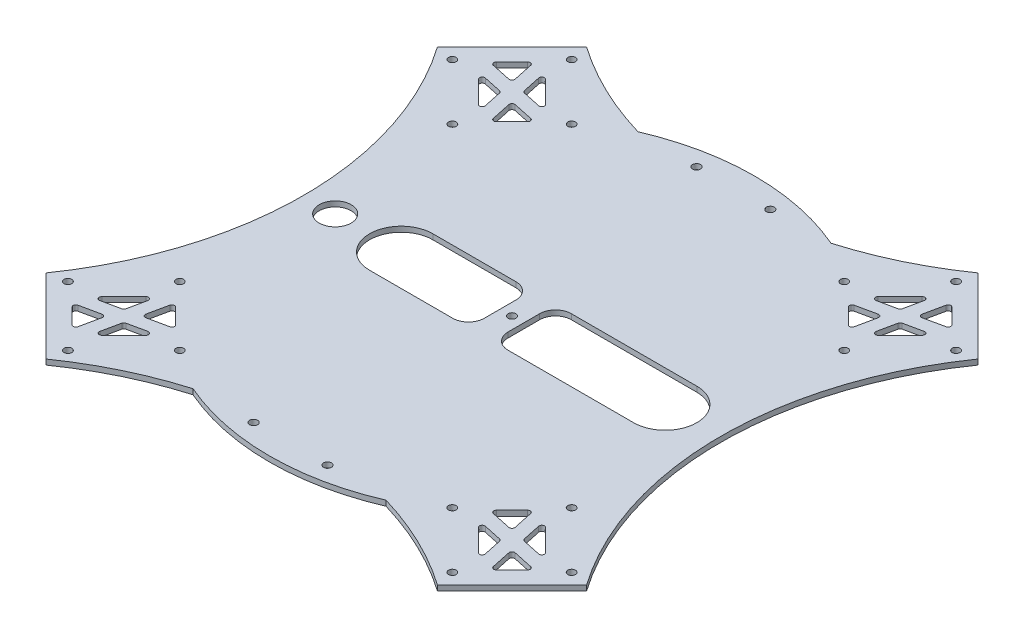
SolidWorks part; units mm, degrees
material "Thornel Mat VMA"
ref_plane "前视基准面" through (0, 0, 0) normal (0, 0, 1) x (1, 0, 0)
ref_plane "上视基准面" through (0, 0, 0) normal (0, 1, 0) x (1, 0, 0)
ref_plane "右视基准面" through (0, 0, 0) normal (1, 0, 0) x (0, 0, -1)
sketch "草图1" plane through (0, 0, 0) normal (0, 1, 0) x (1, 0, 0)
  line L0 (-74.2462, 102.5305) -> (-102.5305, 74.2462)
  line L1 (74.2462, 102.5305) -> (-74.2462, 102.5305)
  line L2 (102.5305, 74.2462) -> (102.5305, -74.2462)
  line L3 (74.2462, -102.5305) -> (-74.2462, -102.5305)
  line L4 (-102.5305, 74.2462) -> (-102.5305, -74.2462)
  line L5 (102.5305, 102.5305) -> (-102.5305, -102.5305) construction
  line L6 (102.5305, -102.5305) -> (-102.5305, 102.5305) construction
  line L7 (102.5305, -74.2462) -> (74.2462, -102.5305)
  line L8 (-102.5305, -74.2462) -> (-74.2462, -102.5305)
  line L9 (74.2462, 102.5305) -> (102.5305, 74.2462)
  line L10 (-102.5305, 102.5305) -> (-102.5305, -102.5305) construction
  line L11 (-102.5305, -102.5305) -> (102.5305, -102.5305) construction
  line L12 (102.5305, -102.5305) -> (102.5305, 102.5305) construction
  line L13 (102.5305, 102.5305) -> (-102.5305, 102.5305) construction
  point P0 (0, 0)
  dimension "D1" = 250
  dimension "D2" = 40
extrude "凸台-拉伸1" add sketch "草图1" along normal blind 2
hole_wizard "孔1" positions "草图4" profile "草图5" legacy
sketch "草图4" plane through (0, 2, 0) normal (0, 1, 0) x (1, 0, 0)
  point P0 (-95.5397, 72.9159)
  point P3 (-74.3265, 51.7027)
  point P6 (-51.6991, 74.3301)
  point P9 (-72.9123, 95.5433)
  point P16 (72.9159, 95.5397)
  point P17 (51.7027, 74.3265)
  point P18 (74.3301, 51.6991)
  point P19 (95.5433, 72.9123)
  point P20 (95.5397, -72.9159)
  point P21 (74.3265, -51.7027)
  point P22 (51.6991, -74.3301)
  point P23 (72.9123, -95.5433)
  point P24 (-72.9159, -95.5397)
  point P25 (-51.7027, -74.3265)
  point P26 (-74.3301, -51.6991)
  point P27 (-95.5433, -72.9123)
  dimension "D1" = 4
sketch "草图5" plane through (-95.5397, 2, -72.9159) normal (1, 0, 0) x (0, 0, 1)
  line L0 (0, 0) -> (0, 100)
  line L1 (0, 100) -> (1.45, 100)
  line L2 (1.45, 100) -> (1.45, 0)
  line L3 (1.45, 0) -> (0, 0)
  line L4 (0, 110) -> (0, -10) construction
  dimension "直径" = 2.9
  dimension "深度" = 100
sketch "草图7" plane through (0, 2, 0) normal (0, 1, 0) x (1, 0, 0)
  line L0 (-95.5397, 72.9159) -> (-51.6991, 74.3301) construction
  line L1 (-86.393, 80.4842) -> (-80.4806, 86.3966)
  line L2 (-84.1601, 71.4358) -> (-75.8066, 63.0823)
  line L3 (-71.4322, 84.1637) -> (-63.0787, 75.8102)
  line L4 (-66.7582, 60.8494) -> (-60.8458, 66.7618)
  line L5 (-89.8008, 77.0764) -> (-57.438, 70.1696) construction
  line L6 (-77.0728, 89.8044) -> (-70.166, 57.4416) construction
  line L7 (-49.2242, 67.6126) -> (-79.6109, 97.9993) construction
  line L8 (-74.2462, 102.5305) -> (-102.5305, 74.2462) construction
  line L9 (-85.8946, 78.7991) -> (-78.378, 77.1949)
  line L10 (-83.2443, 73.1208) -> (-76.36, 71.6516)
  line L11 (-87.6941, 79.1831) -> (-89.8008, 77.0764) construction
  line L12 (-89.8008, 77.0764) -> (-86.5509, 73.8265) construction
  line L13 (-60.6879, 73.4195) -> (-57.438, 70.1696) construction
  line L14 (-57.438, 70.1696) -> (-59.5447, 68.0629) construction
  line L15 (-67.4604, 74.8648) -> (-68.504, 69.975) construction
  line L16 (-73.6194, 73.623) -> (-67.2554, 79.987) construction
  line L17 (-74.1216, 63.9981) -> (-75.5908, 70.8824)
  line L18 (-68.4433, 61.3478) -> (-70.0475, 68.8644)
  line L19 (-70.8788, 75.5944) -> (-63.9945, 74.1252)
  line L20 (-77.1913, 78.3816) -> (-78.7955, 85.8982)
  line L21 (-68.8608, 70.0511) -> (-61.3442, 68.4469)
  line L22 (-71.648, 76.3636) -> (-73.1172, 83.2479)
  line L23 (80.4842, 86.393) -> (86.3966, 80.4806)
  line L24 (71.4358, 84.1601) -> (63.0823, 75.8066)
  line L25 (84.1637, 71.4322) -> (75.8102, 63.0787)
  line L26 (60.8494, 66.7582) -> (66.7618, 60.8458)
  line L27 (78.7991, 85.8946) -> (77.1949, 78.378)
  line L28 (73.1208, 83.2443) -> (71.6516, 76.36)
  line L29 (63.9981, 74.1216) -> (70.8824, 75.5908)
  line L30 (61.3478, 68.4433) -> (68.8644, 70.0475)
  line L31 (75.5944, 70.8788) -> (74.1252, 63.9945)
  line L32 (78.3816, 77.1913) -> (85.8982, 78.7955)
  line L33 (70.0511, 68.8608) -> (68.4469, 61.3442)
  line L34 (76.3636, 71.648) -> (83.2479, 73.1172)
  line L35 (72.9159, 95.5397) -> (74.3301, 51.6991) construction
  line L36 (77.0764, 89.8008) -> (70.1696, 57.438) construction
  line L37 (89.8044, 77.0728) -> (57.4416, 70.166) construction
  line L38 (79.1831, 87.6941) -> (77.0764, 89.8008) construction
  line L39 (77.0764, 89.8008) -> (73.8265, 86.5509) construction
  line L40 (73.4195, 60.6879) -> (70.1696, 57.438) construction
  line L41 (70.1696, 57.438) -> (68.0629, 59.5447) construction
  line L42 (74.8648, 67.4604) -> (69.975, 68.504) construction
  line L43 (73.623, 73.6194) -> (79.987, 67.2554) construction
  line L44 (86.393, -80.4842) -> (80.4806, -86.3966)
  line L45 (84.1601, -71.4358) -> (75.8066, -63.0823)
  line L46 (71.4322, -84.1637) -> (63.0787, -75.8102)
  line L47 (66.7582, -60.8494) -> (60.8458, -66.7618)
  line L48 (85.8946, -78.7991) -> (78.378, -77.1949)
  line L49 (83.2443, -73.1208) -> (76.36, -71.6516)
  line L50 (74.1216, -63.9981) -> (75.5908, -70.8824)
  line L51 (68.4433, -61.3478) -> (70.0475, -68.8644)
  line L52 (70.8788, -75.5944) -> (63.9945, -74.1252)
  line L53 (77.1913, -78.3816) -> (78.7955, -85.8982)
  line L54 (68.8608, -70.0511) -> (61.3442, -68.4469)
  line L55 (71.648, -76.3636) -> (73.1172, -83.2479)
  line L56 (95.5397, -72.9159) -> (51.6991, -74.3301) construction
  line L57 (89.8008, -77.0764) -> (57.438, -70.1696) construction
  line L58 (77.0728, -89.8044) -> (70.166, -57.4416) construction
  line L59 (87.6941, -79.1831) -> (89.8008, -77.0764) construction
  line L60 (89.8008, -77.0764) -> (86.5509, -73.8265) construction
  line L61 (60.6879, -73.4195) -> (57.438, -70.1696) construction
  line L62 (57.438, -70.1696) -> (59.5447, -68.0629) construction
  line L63 (67.4604, -74.8648) -> (68.504, -69.975) construction
  line L64 (73.6194, -73.623) -> (67.2554, -79.987) construction
  line L65 (-80.4842, -86.393) -> (-86.3966, -80.4806)
  line L66 (-71.4358, -84.1601) -> (-63.0823, -75.8066)
  line L67 (-84.1637, -71.4322) -> (-75.8102, -63.0787)
  line L68 (-60.8494, -66.7582) -> (-66.7618, -60.8458)
  line L69 (-78.7991, -85.8946) -> (-77.1949, -78.378)
  line L70 (-73.1208, -83.2443) -> (-71.6516, -76.36)
  line L71 (-63.9981, -74.1216) -> (-70.8824, -75.5908)
  line L72 (-61.3478, -68.4433) -> (-68.8644, -70.0475)
  line L73 (-75.5944, -70.8788) -> (-74.1252, -63.9945)
  line L74 (-78.3816, -77.1913) -> (-85.8982, -78.7955)
  line L75 (-70.0511, -68.8608) -> (-68.4469, -61.3442)
  line L76 (-76.3636, -71.648) -> (-83.2479, -73.1172)
  line L77 (-72.9159, -95.5397) -> (-74.3301, -51.6991) construction
  line L78 (-77.0764, -89.8008) -> (-70.1696, -57.438) construction
  line L79 (-89.8044, -77.0728) -> (-57.4416, -70.166) construction
  line L80 (-79.1831, -87.6941) -> (-77.0764, -89.8008) construction
  line L81 (-77.0764, -89.8008) -> (-73.8265, -86.5509) construction
  line L82 (-73.4195, -60.6879) -> (-70.1696, -57.438) construction
  line L83 (-70.1696, -57.438) -> (-68.0629, -59.5447) construction
  line L84 (-74.8648, -67.4604) -> (-69.975, -68.504) construction
  line L85 (-73.623, -73.6194) -> (-79.987, -67.2554) construction
  arc A0 (-63.0787, 75.8102) -> (-63.9945, 74.1252) centre (-63.7858, 75.1031) cw
  arc A1 (-70.8788, 75.5944) -> (-71.648, 76.3636) centre (-70.67, 76.5724) cw
  arc A2 (-71.4322, 84.1637) -> (-73.1172, 83.2479) centre (-72.1393, 83.4566) ccw
  arc A3 (-78.7955, 85.8982) -> (-80.4806, 86.3966) centre (-79.7735, 85.6895) ccw
  arc A4 (-85.8946, 78.7991) -> (-86.393, 80.4842) centre (-85.6859, 79.7771) cw
  arc A5 (-78.378, 77.1949) -> (-77.1913, 78.3816) centre (-78.1693, 78.1729) ccw
  arc A6 (-66.7582, 60.8494) -> (-68.4433, 61.3478) centre (-67.4653, 61.5565) cw
  arc A7 (-60.8458, 66.7618) -> (-61.3442, 68.4469) centre (-61.5529, 67.4689) ccw
  arc A8 (-68.8608, 70.0511) -> (-70.0475, 68.8644) centre (-69.0695, 69.0731) ccw
  arc A9 (-75.8066, 63.0823) -> (-74.1216, 63.9981) centre (-75.0995, 63.7894) ccw
  arc A10 (-75.5908, 70.8824) -> (-76.36, 71.6516) centre (-76.5688, 70.6736) ccw
  arc A11 (-83.2443, 73.1208) -> (-84.1601, 71.4358) centre (-83.453, 72.1429) ccw
  arc A12 (75.8102, 63.0787) -> (74.1252, 63.9945) centre (75.1031, 63.7858) cw
  arc A13 (75.5944, 70.8788) -> (76.3636, 71.648) centre (76.5724, 70.67) cw
  arc A14 (84.1637, 71.4322) -> (83.2479, 73.1172) centre (83.4566, 72.1393) ccw
  arc A15 (85.8982, 78.7955) -> (86.3966, 80.4806) centre (85.6895, 79.7735) ccw
  arc A16 (78.7991, 85.8946) -> (80.4842, 86.393) centre (79.7771, 85.6859) cw
  arc A17 (77.1949, 78.378) -> (78.3816, 77.1913) centre (78.1729, 78.1693) ccw
  arc A18 (60.8494, 66.7582) -> (61.3478, 68.4433) centre (61.5565, 67.4653) cw
  arc A19 (66.7618, 60.8458) -> (68.4469, 61.3442) centre (67.4689, 61.5529) ccw
  arc A20 (70.0511, 68.8608) -> (68.8644, 70.0475) centre (69.0731, 69.0695) ccw
  arc A21 (63.0823, 75.8066) -> (63.9981, 74.1216) centre (63.7894, 75.0995) ccw
  arc A22 (70.8824, 75.5908) -> (71.6516, 76.36) centre (70.6736, 76.5688) ccw
  arc A23 (73.1208, 83.2443) -> (71.4358, 84.1601) centre (72.1429, 83.453) ccw
  arc A24 (63.0787, -75.8102) -> (63.9945, -74.1252) centre (63.7858, -75.1031) cw
  arc A25 (70.8788, -75.5944) -> (71.648, -76.3636) centre (70.67, -76.5724) cw
  arc A26 (71.4322, -84.1637) -> (73.1172, -83.2479) centre (72.1393, -83.4566) ccw
  arc A27 (78.7955, -85.8982) -> (80.4806, -86.3966) centre (79.7735, -85.6895) ccw
  arc A28 (85.8946, -78.7991) -> (86.393, -80.4842) centre (85.6859, -79.7771) cw
  arc A29 (78.378, -77.1949) -> (77.1913, -78.3816) centre (78.1693, -78.1729) ccw
  arc A30 (66.7582, -60.8494) -> (68.4433, -61.3478) centre (67.4653, -61.5565) cw
  arc A31 (60.8458, -66.7618) -> (61.3442, -68.4469) centre (61.5529, -67.4689) ccw
  arc A32 (68.8608, -70.0511) -> (70.0475, -68.8644) centre (69.0695, -69.0731) ccw
  arc A33 (75.8066, -63.0823) -> (74.1216, -63.9981) centre (75.0995, -63.7894) ccw
  arc A34 (75.5908, -70.8824) -> (76.36, -71.6516) centre (76.5688, -70.6736) ccw
  arc A35 (83.2443, -73.1208) -> (84.1601, -71.4358) centre (83.453, -72.1429) ccw
  arc A36 (-75.8102, -63.0787) -> (-74.1252, -63.9945) centre (-75.1031, -63.7858) cw
  arc A37 (-75.5944, -70.8788) -> (-76.3636, -71.648) centre (-76.5724, -70.67) cw
  arc A38 (-84.1637, -71.4322) -> (-83.2479, -73.1172) centre (-83.4566, -72.1393) ccw
  arc A39 (-85.8982, -78.7955) -> (-86.3966, -80.4806) centre (-85.6895, -79.7735) ccw
  arc A40 (-78.7991, -85.8946) -> (-80.4842, -86.393) centre (-79.7771, -85.6859) cw
  arc A41 (-77.1949, -78.378) -> (-78.3816, -77.1913) centre (-78.1729, -78.1693) ccw
  arc A42 (-60.8494, -66.7582) -> (-61.3478, -68.4433) centre (-61.5565, -67.4653) cw
  arc A43 (-66.7618, -60.8458) -> (-68.4469, -61.3442) centre (-67.4689, -61.5529) ccw
  arc A44 (-70.0511, -68.8608) -> (-68.8644, -70.0475) centre (-69.0731, -69.0695) ccw
  arc A45 (-63.0823, -75.8066) -> (-63.9981, -74.1216) centre (-63.7894, -75.0995) ccw
  arc A46 (-70.8824, -75.5908) -> (-71.6516, -76.36) centre (-70.6736, -76.5688) ccw
  arc A47 (-73.1208, -83.2443) -> (-71.4358, -84.1601) centre (-72.1429, -83.453) ccw
  point P5 (-73.6194, 73.623)
  point P14 (-72.9123, 95.5433)
  point P21 (-67.9822, 72.4199)
  point P38 (-71.5127, 75.7297)
  point P41 (-73.8229, 86.5545)
  point P44 (-79.1795, 87.6977)
  point P50 (-76.8693, 76.8729)
  point P53 (-68.0593, 59.5483)
  point P59 (-70.3695, 70.3731)
  point P62 (-73.4159, 60.6915)
  point P73 (73.623, 73.6194)
  point P84 (72.4199, 67.9822)
  point P126 (73.6194, -73.623)
  point P137 (67.9822, -72.4199)
  point P179 (-73.623, -73.6194)
  point P190 (-72.4199, -67.9822)
  point P230 (0, 0)
  dimension "D4" = 1
  dimension "D1" = 7
  dimension "D2" = 7
  dimension "D3" = 5
  dimension "D5" = 4
extrude "切除-拉伸2" cut sketch "草图7" against normal through all both and the other way through all
sketch "草图8" plane through (0, 2, 0) normal (0, 1, 0) x (1, 0, 0)
  line L0 (-208.5651, 0) -> (0, 0) construction
  line L1 (-102.5305, -74.2462) -> (-50.5427, 0) construction
  line L3 (0, 0) -> (-88.3883, -88.3883) construction
  line L4 (-102.5305, -74.2462) -> (-74.2462, -102.5305) construction
  line L5 (0, 102.5305) -> (0, -102.5305) construction
  line L6 (74.2462, 102.5305) -> (-74.2462, 102.5305) construction
  line L7 (-74.2462, -102.5305) -> (74.2462, -102.5305) construction
  circle A0 centre (-208.5651, 0) radius 129.4443
  circle A2 centre (0, 208.5651) radius 129.4443
  circle A3 centre (208.5651, 0) radius 129.4443
  circle A4 centre (0, -208.5651) radius 129.4443
  point P28 (0, 0)
  dimension "D1" = 10
  dimension "D2" = 4
extrude "切除-拉伸3" cut sketch "草图8" against normal through all both and the other way through all
sketch "草图9" plane through (0, 2, 0) normal (0, 1, 0) x (1, 0, 0)
  line L0 (0, 0) -> (-79.1207, 0) construction
  arc A0 (-102.5305, -74.2462) -> (-102.5305, 74.2462) centre (-208.5651, 0) ccw construction
  circle A1 centre (-67.0707, 0) radius 6.05
  point P8 (-73.1207, 0)
  dimension "D1" = 12.1
  dimension "D2" = 6
extrude "切除-拉伸4" cut sketch "草图9" against normal through all both and the other way through all
sketch "草图12" plane through (0, 2, 0) normal (0, 1, 0) x (1, 0, 0)
  line L0 (-74.2462, 102.5305) -> (-19.9669, 133.265)
  line L1 (-17.0105, 134.0438) -> (17.0105, 134.0438)
  line L2 (19.9669, 133.265) -> (74.2462, 102.5305)
  line L3 (0, 134.0438) -> (0, 0) construction
  line L4 (-74.2462, 102.5305) -> (-66.3304, 96.7253)
  line L5 (-62.6332, 98.7635) -> (-17.5957, 124.265)
  line L6 (-14.6394, 125.0438) -> (-10.5, 125.0438)
  line L7 (17.5957, 124.265) -> (62.6332, 98.7635)
  line L8 (66.1574, 95.9526) -> (74.2462, 102.5305)
  line L9 (-4.5, 119.0438) -> (-4.5, 81.2866)
  line L10 (-9.698, 64.0438) -> (9.698, 64.0438)
  line L11 (4.5, 81.2866) -> (4.5, 119.0438)
  line L12 (10.5, 125.0438) -> (14.6394, 125.0438)
  line L13 (-46.2735, 118.3694) -> (-41.839, 110.5377) construction
  line L14 (-4.5, 125.0438) -> (-4.5, 134.0438) construction
  line L15 (-66.3304, 96.7253) -> (-9.698, 64.0438)
  line L16 (9.698, 64.0438) -> (66.1574, 95.9526)
  line L17 (-4.5, 79.199) -> (4.5, 79.199) construction
  line L18 (-79.1207, 0) -> (79.1207, 0) construction
  line L19 (-4.5, -79.199) -> (4.5, -79.199) construction
  line L20 (-4.5, -125.0438) -> (-4.5, -134.0438) construction
  line L21 (-46.2735, -118.3694) -> (-41.839, -110.5377) construction
  line L22 (9.698, -64.0438) -> (66.1574, -95.9526)
  line L23 (-66.3304, -96.7253) -> (-9.698, -64.0438)
  line L24 (10.5, -125.0438) -> (14.6394, -125.0438)
  line L25 (4.5, -81.2866) -> (4.5, -119.0438)
  line L26 (-9.698, -64.0438) -> (9.698, -64.0438)
  line L27 (-4.5, -119.0438) -> (-4.5, -81.2866)
  line L28 (66.1574, -95.9526) -> (74.2462, -102.5305)
  line L29 (17.5957, -124.265) -> (62.6332, -98.7635)
  line L30 (-14.6394, -125.0438) -> (-10.5, -125.0438)
  line L31 (-62.6332, -98.7635) -> (-17.5957, -124.265)
  line L32 (-74.2462, -102.5305) -> (-66.3304, -96.7253)
  line L33 (19.9669, -133.265) -> (74.2462, -102.5305)
  line L34 (-17.0105, -134.0438) -> (17.0105, -134.0438)
  line L35 (-74.2462, -102.5305) -> (-19.9669, -133.265)
  arc A0 (-62.6152, 95.2727) -> (-6.602, 79.2892) centre (0, 208.5651) ccw
  arc A1 (-74.2462, 102.5305) -> (74.2462, 102.5305) centre (0, 208.5651) ccw construction
  arc A2 (6.602, 79.2892) -> (62.6152, 95.2727) centre (0, 208.5651) ccw
  arc A3 (-102.5305, -74.2462) -> (-102.5305, 74.2462) centre (-208.5651, 0) ccw construction
  arc A4 (102.5305, 74.2462) -> (102.5305, -74.2462) centre (208.5651, 0) ccw construction
  arc A5 (62.6152, 95.2727) -> (62.6332, 98.7635) centre (61.6478, 97.0231) ccw
  arc A6 (-62.6332, 98.7635) -> (-62.6152, 95.2727) centre (-61.6478, 97.0231) ccw
  arc A7 (6.602, 79.2892) -> (4.5, 81.2866) centre (6.5, 81.2866) cw
  arc A8 (-4.5, 81.2866) -> (-6.602, 79.2892) centre (-6.5, 81.2866) cw
  arc A9 (19.9669, 133.265) -> (17.0105, 134.0438) centre (17.0105, 128.0438) ccw
  arc A10 (-17.0105, 134.0438) -> (-19.9669, 133.265) centre (-17.0105, 128.0438) ccw
  arc A11 (-14.6394, 125.0438) -> (-17.5957, 124.265) centre (-14.6394, 119.0438) ccw
  arc A12 (17.5957, 124.265) -> (14.6394, 125.0438) centre (14.6394, 119.0438) ccw
  arc A13 (4.5, 119.0438) -> (10.5, 125.0438) centre (10.5, 119.0438) cw
  arc A14 (-4.5, 119.0438) -> (-10.5, 125.0438) centre (-10.5, 119.0438) ccw
  arc A15 (-4.5, -119.0438) -> (-10.5, -125.0438) centre (-10.5, -119.0438) cw
  arc A16 (4.5, -119.0438) -> (10.5, -125.0438) centre (10.5, -119.0438) ccw
  arc A17 (17.5957, -124.265) -> (14.6394, -125.0438) centre (14.6394, -119.0438) cw
  arc A18 (-14.6394, -125.0438) -> (-17.5957, -124.265) centre (-14.6394, -119.0438) cw
  arc A19 (-17.0105, -134.0438) -> (-19.9669, -133.265) centre (-17.0105, -128.0438) cw
  arc A20 (19.9669, -133.265) -> (17.0105, -134.0438) centre (17.0105, -128.0438) cw
  arc A21 (-4.5, -81.2866) -> (-6.602, -79.2892) centre (-6.5, -81.2866) ccw
  arc A22 (6.602, -79.2892) -> (4.5, -81.2866) centre (6.5, -81.2866) ccw
  arc A23 (-62.6332, -98.7635) -> (-62.6152, -95.2727) centre (-61.6478, -97.0231) cw
  arc A24 (62.6152, -95.2727) -> (62.6332, -98.7635) centre (61.6478, -97.0231) cw
  arc A25 (6.602, -79.2892) -> (62.6152, -95.2727) centre (0, -208.5651) cw
  arc A26 (-62.6152, -95.2727) -> (-6.602, -79.2892) centre (0, -208.5651) cw
  point P17 (0, 64.0438)
  point P24 (0, 79.199)
  point P40 (65.6946, 97.0301)
  point P43 (-65.6946, 97.0301)
  point P60 (4.5, 125.0438)
  point P107 (4.5, -125.0438)
  point P108 (-65.6946, -97.0301)
  point P109 (65.6946, -97.0301)
  point P110 (0, -79.199)
  point P111 (0, -64.0438)
  dimension "D4" = 2
  dimension "D5" = 2
  dimension "D6" = 6
  dimension "D1" = 70
  dimension "D2" = 9
  dimension "D3" = 9
sketch "草图15" plane through (0, 2, 0) normal (0, 1, 0) x (1, 0, 0)
  line L1 (-40.3412, 82.6837) -> (-31.9185, 62.6852)
  line L2 (44.6358, 80.4465) -> (36.2732, 60.2701)
  line L3 (-42.4295, -81.6317) -> (-34.5316, -61.2845)
  line L4 (41.391, -82.1632) -> (34.5498, -61.2743)
  arc A0 (-42.4295, -81.6317) -> (41.391, -82.1632) centre (0, 0) ccw
  arc A2 (-34.5316, -61.2845) -> (34.5498, -61.2743) centre (0, 0) ccw
  arc A3 (36.2732, 60.2701) -> (-31.9185, 62.6852) centre (0, 0) ccw
  arc A4 (44.6358, 80.4465) -> (-40.3412, 82.6837) centre (0, 0) ccw
  dimension "D1" = 92
extrude "凸台-拉伸3" add sketch "草图15" against normal up to surface (2 mm away) up to face at (-67.0707, 0, 6.05)
hole_wizard "孔2" positions "草图16" profile "草图17" legacy
sketch "草图16" plane through (0, 2, 0) normal (0, 1, 0) x (1, 0, 0)
  line L0 (-14, 84) -> (14, 84) construction
  line L3 (0, 84) -> (0, -129.5438) construction
  line L6 (-61.0207, 0) -> (79.1207, 0) construction
  circle A0 centre (-67.0707, 0) radius 6.05 construction
  arc A1 (102.5305, 74.2462) -> (102.5305, -74.2462) centre (208.5651, 0) ccw construction
  point P0 (-14, 84)
  point P3 (14, 84)
  point P66 (79.1207, 0)
  point P70 (0, 0)
  point P71 (-14, -84)
  point P72 (14, -84)
  dimension "D1" = 28
  dimension "D3" = 84
sketch "草图17" plane through (-14, 2, -84) normal (1, 0, 0) x (0, 0, 1)
  line L0 (0, 0) -> (0, 100)
  line L1 (0, 100) -> (1.5, 100)
  line L2 (1.5, 100) -> (1.5, 0)
  line L3 (1.5, 0) -> (0, 0)
  line L4 (0, 110) -> (0, -10) construction
  dimension "直径" = 3
  dimension "深度" = 100
sketch "草图18" plane through (0, 2, 0) normal (0, 1, 0) x (1, 0, 0)
  line L0 (-42.0207, 0) -> (58.1207, 0) construction
  line L1 (-42.0207, 12) -> (-10.5, 12)
  line L2 (-42.0207, -12) -> (-10.5, -12)
  line L3 (-54.0207, 0) -> (-79.1207, 0) construction
  line L4 (10.5, -12) -> (58.1207, -12)
  line L5 (-4.5, -12) -> (4.5, -12) construction
  line L6 (-4.5, 6) -> (-4.5, -6)
  line L7 (10.5, 12) -> (58.1207, 12)
  line L8 (4.5, 6) -> (4.5, -6)
  line L9 (-4.5, 12) -> (4.5, -12) construction
  line L10 (-4.5, -12) -> (4.5, 12) construction
  line L11 (-4.5, 12) -> (4.5, 12) construction
  arc A0 (-42.0207, 12) -> (-42.0207, -12) centre (-42.0207, 0) ccw
  arc A1 (58.1207, -12) -> (58.1207, 12) centre (58.1207, 0) ccw
  arc A2 (102.5305, 74.2462) -> (102.5305, -74.2462) centre (208.5651, 0) ccw construction
  arc A3 (-10.5, 12) -> (-4.5, 6) centre (-10.5, 6) cw
  arc A4 (-102.5305, -74.2462) -> (-102.5305, 74.2462) centre (-208.5651, 0) ccw construction
  circle A5 centre (-67.0707, 0) radius 6.05 construction
  arc A6 (10.5, 12) -> (4.5, 6) centre (10.5, 6) ccw
  arc A7 (10.5, -12) -> (4.5, -6) centre (10.5, -6) cw
  arc A8 (-4.5, -6) -> (-10.5, -12) centre (-10.5, -6) cw
  circle A9 centre (0, 0) radius 1.5
  point P3 (0, 0)
  point P8 (70.1207, 0)
  point P9 (79.1207, 0)
  point P10 (-61.0207, 0)
  point P14 (-54.0207, 0)
  point P15 (0, 0)
  dimension "D3" = 12
  dimension "D5" = 6
  dimension "D6" = 3
  dimension "D1" = 9
  dimension "D2" = 7
  dimension "D4" = 9
extrude "切除-拉伸5" cut sketch "草图18" against normal through all both and the other way through all
